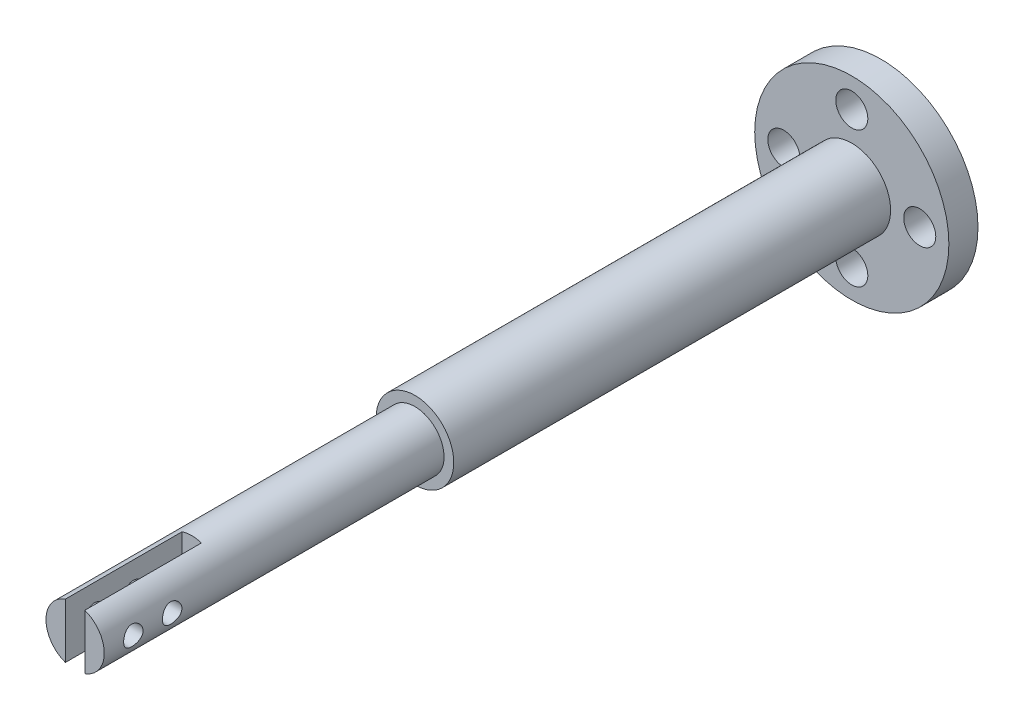
SolidWorks part; units mm, degrees
ref_plane "前视基准面" through (0, 0, 0) normal (0, 0, 1) x (1, 0, 0)
ref_plane "上视基准面" through (0, 0, 0) normal (0, 1, 0) x (1, 0, 0)
ref_plane "右视基准面" through (0, 0, 0) normal (1, 0, 0) x (0, 0, -1)
sketch "草图1" plane through (0, 0, 0) normal (0, 0, 1) x (1, 0, 0)
  line L0 (-10, 0) -> (10, 0) construction
  line L1 (0, 10) -> (0, -10.2805) construction
  circle A0 centre (0, 0) radius 10
  circle A1 centre (0, 7) radius 1.65
  circle A2 centre (7, 0) radius 1.65
  circle A3 centre (0, -7) radius 1.65
  circle A4 centre (-7, 0) radius 1.65
  dimension "D1" = 20
  dimension "D2" = 3.3
  dimension "D3" = 3.3
  dimension "D4" = 3.3
  dimension "D5" = 3.3
  dimension "D6" = 7
  dimension "D7" = 7
  dimension "D8" = 7
  dimension "D9" = 7
extrude "凸台-拉伸1" add sketch "草图1" along normal blind 3
sketch "草图2" plane through (0, 0, 3) normal (0, 0, 1) x (1, 0, 0)
  circle A0 centre (0, 0) radius 3
  dimension "D1" = 6
extrude "凸台-拉伸2" add sketch "草图2" along normal blind 80
sketch "草图3" plane through (0, 0, 83) normal (0, 0, 1) x (1, 0, 0)
  line L1 (-1, -3.8717) -> (1, -3.8717)
  line L2 (-1, -3.8717) -> (-1, 3.8717)
  line L3 (-1, 3.8717) -> (1, 3.8717)
  line L4 (1, -3.8717) -> (1, 3.8717)
  line L5 (-1, -3.8717) -> (1, 3.8717) construction
  line L6 (-1, 3.8717) -> (1, -3.8717) construction
  point P0 (0, 0)
  dimension "D1" = 7.7434
  dimension "D2" = 2
extrude "切除-拉伸1" cut sketch "草图3" against normal blind 12
sketch "草图5" plane through (-1, 0, 0) normal (1, 0, 0) x (0, 0, -1)
  line L0 (-83, 2.8284) -> (-83, -2.8284) construction
  line L1 (-83, 0) -> (-71.6344, 0) construction
  circle A0 centre (-80, 0) radius 1
  circle A1 centre (-76, 0) radius 1
  point P9 (0, 0)
  dimension "D1" = 2
  dimension "D2" = 2
  dimension "D3" = 3
  dimension "D4" = 4
extrude "切除-拉伸2" cut sketch "草图5" against normal mid plane 10
sketch "草图6" plane through (0, 0, 3) normal (0, 0, 1) x (1, 0, 0)
  circle A0 centre (0, 0) radius 4
  dimension "D1" = 8
extrude "凸台-拉伸3" add sketch "草图6" along normal blind 45
